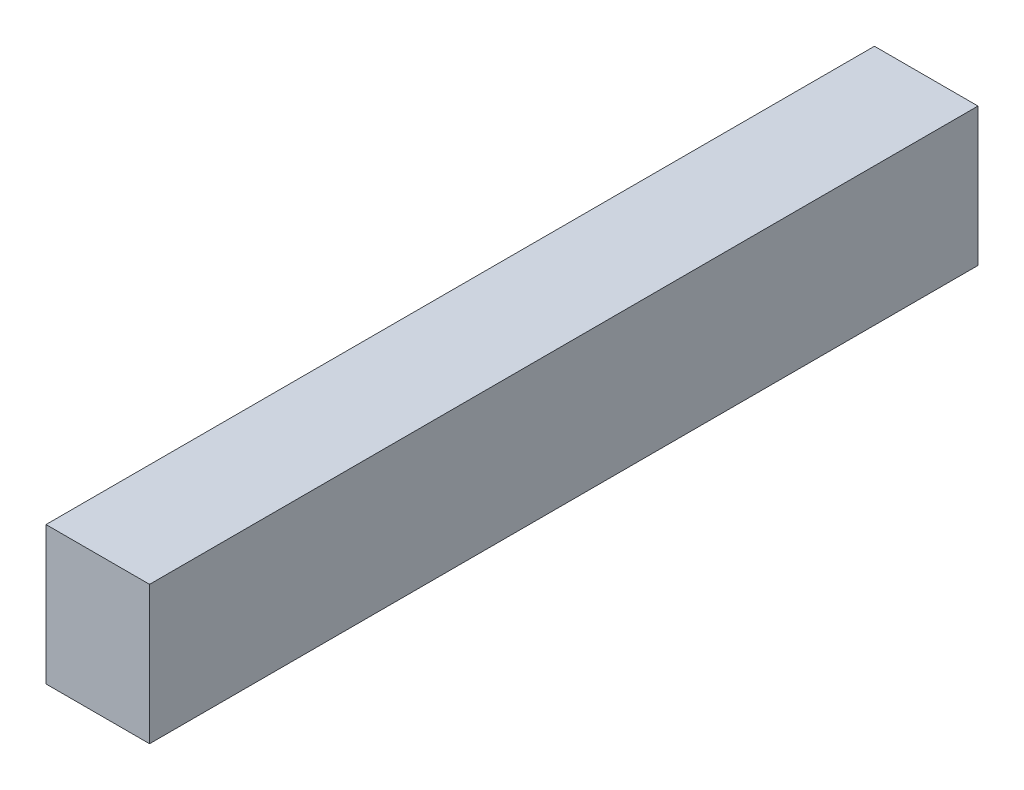
SolidWorks part; units mm, degrees
material "1060 Alloy"
ref_plane "Front Plane" through (0, 0, 0) normal (0, 0, 1) x (1, 0, 0)
ref_plane "Top Plane" through (0, 0, 0) normal (0, 1, 0) x (1, 0, 0)
ref_plane "Right Plane" through (0, 0, 0) normal (1, 0, 0) x (0, 0, -1)
sketch "Sketch1" plane through (0, 0, 0) normal (0, 0, 1) x (1, 0, 0)
  line L1 (-4.2022, 5.0426) -> (5.3228, 5.0426)
  line L2 (-4.2022, 5.0426) -> (-4.2022, -7.6574)
  line L3 (-4.2022, -7.6574) -> (5.3228, -7.6574)
  line L4 (5.3228, 5.0426) -> (5.3228, -7.6574)
  dimension "D1" = 12.7
  dimension "D2" = 9.525
extrude "Boss-Extrude1" add sketch "Sketch1" along normal blind 76.2
